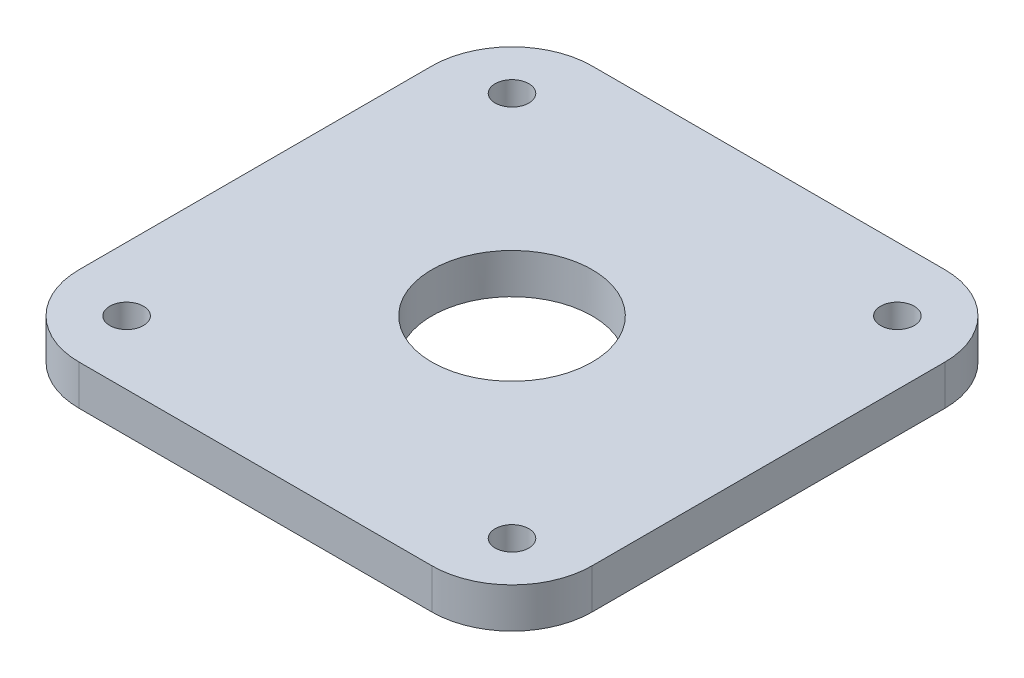
SolidWorks part; units mm, degrees
ref_plane "前视基准面" through (0, 0, 0) normal (0, 0, 1) x (1, 0, 0)
ref_plane "上视基准面" through (0, 0, 0) normal (0, 1, 0) x (1, 0, 0)
ref_plane "右视基准面" through (0, 0, 0) normal (1, 0, 0) x (0, 0, -1)
other "Configuration Table"
sketch "草图1" plane through (0, 0, 0) normal (0, 1, 0) x (1, 0, 0)
  line L1 (-32, -32) -> (32, -32)
  line L2 (-32, -32) -> (-32, 32)
  line L3 (-32, 32) -> (32, 32)
  line L4 (32, -32) -> (32, 32)
  line L5 (-32, -32) -> (32, 32) construction
  line L6 (-32, 32) -> (32, -32) construction
  point P0 (0, 0)
  dimension "D1" = 64
extrude "凸台-拉伸1" add sketch "草图1" along normal blind 5
sketch "草图2" plane through (0, 5, 0) normal (0, 1, 0) x (1, 0, 0)
  circle A0 centre (0, 0) radius 10
  dimension "D1" = 20
fillet "圆角1" radius 10 4 edges at (32, 2.5, -32) (32, 2.5, 32) (-32, 2.5, 32) (-32, 2.5, -32)
sketch "草图3" plane through (0, 5, 0) normal (0, 1, 0) x (1, 0, 0)
  line L0 (0, 0) -> (34.2804, 34.2804) construction
  line L1 (0, 0) -> (45.0493, 0) construction
  circle A0 centre (0, 0) radius 34 construction
  circle A1 centre (24.0416, 24.0416) radius 2.1
  circle A2 centre (24.0416, -24.0416) radius 2.1
  circle A3 centre (-24.0416, -24.0416) radius 2.1
  circle A4 centre (-24.0416, 24.0416) radius 2.1
  dimension "D2" = 4.2
  dimension "D3" = 68
  dimension "D1" = 45
  dimension "D4" = 4
extrude "切除-拉伸2" cut sketch "草图3" against normal blind 10
extrude "切除-拉伸3" cut sketch "草图2" against normal blind 20
